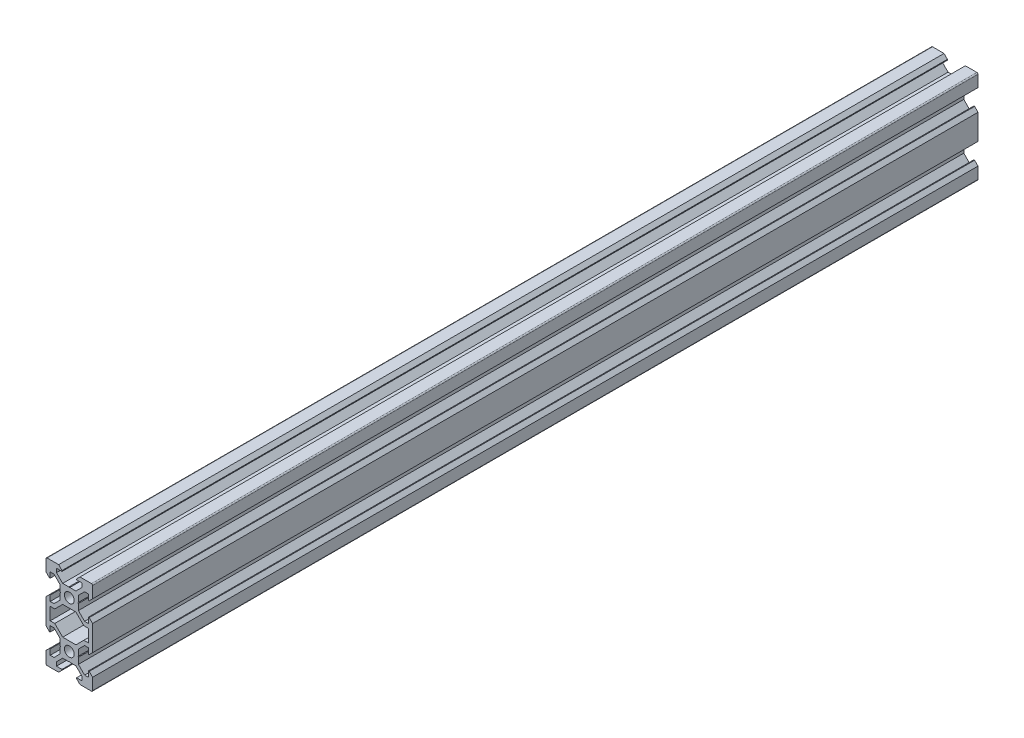
SolidWorks part; units mm, degrees
ref_plane "Front Plane" through (0, 0, 0) normal (0, 0, 1) x (1, 0, 0)
ref_plane "Top Plane" through (0, 0, 0) normal (0, 1, 0) x (1, 0, 0)
ref_plane "Right Plane" through (0, 0, 0) normal (1, 0, 0) x (0, 0, -1)
sketch "Sketch2" plane through (0, 0, 0) normal (0, 0, 1) x (1, 0, 0)
  line L106 (-6.1325, -2.3442) -> (-2.7325, -5.7442)
  line L107 (-8.0932, -2.3442) -> (-6.1325, -2.3442)
  line L108 (-8.0932, -2.3442) -> (-8.0932, 3.0558)
  line L109 (-8.0932, 3.0558) -> (-6.1325, 3.0558)
  line L110 (-6.1325, 3.0558) -> (-2.7325, 6.4558)
  line L111 (-2.7325, 6.4558) -> (2.9461, 6.4558)
  line L112 (6.3461, 3.0558) -> (2.9461, 6.4558)
  line L113 (8.3068, 3.0558) -> (6.3461, 3.0558)
  line L114 (8.3068, -2.3442) -> (8.3068, 3.0558)
  line L115 (8.3068, -2.3442) -> (6.3461, -2.3442)
  line L116 (6.3461, -2.3442) -> (2.9461, -5.7442)
  line L117 (-2.7325, -5.7442) -> (2.9461, -5.7442)
  line L118 (4.0068, 10.1458) -> (3.7968, 10.3558)
  line L119 (3.7968, 10.3558) -> (4.0068, 10.5658)
  line L120 (4.0068, 10.5658) -> (4.0068, 13.1951)
  line L121 (4.0068, 13.1951) -> (6.6675, 15.8558)
  line L122 (6.6675, 15.8558) -> (8.3068, 15.8558)
  line L123 (8.3068, 15.8558) -> (8.3068, 13.4808)
  line L124 (8.3068, 13.4808) -> (8.6518, 13.4808)
  line L125 (8.6518, 13.4808) -> (10.1068, 14.9358)
  line L126 (10.1068, 14.9358) -> (10.1068, 19.8558)
  line L127 (9.6068, 20.3558) -> (4.6868, 20.3558)
  line L128 (4.6868, 20.3558) -> (3.2318, 18.9008)
  line L129 (3.2318, 18.9008) -> (3.2318, 18.5558)
  line L130 (3.2318, 18.5558) -> (5.6068, 18.5558)
  line L131 (5.6068, 18.5558) -> (5.6068, 16.9165)
  line L132 (5.6068, 16.9165) -> (2.9461, 14.2558)
  line L133 (2.9461, 14.2558) -> (0.3168, 14.2558)
  line L134 (0.3168, 14.2558) -> (0.1068, 14.0458)
  line L135 (0.1068, 14.0458) -> (-0.1032, 14.2558)
  line L136 (-0.1032, 14.2558) -> (-2.7325, 14.2558)
  line L137 (-2.7325, 14.2558) -> (-5.3932, 16.9165)
  line L138 (-5.3932, 16.9165) -> (-5.3932, 18.5558)
  line L139 (-5.3932, 18.5558) -> (-3.0182, 18.5558)
  line L140 (-3.0182, 18.5558) -> (-3.0182, 18.9008)
  line L141 (-3.0182, 18.9008) -> (-4.4732, 20.3558)
  line L142 (-4.4732, 20.3558) -> (-9.3932, 20.3558)
  line L143 (-9.8932, 19.8558) -> (-9.8932, 14.9358)
  line L144 (-9.8932, 14.9358) -> (-8.4382, 13.4808)
  line L145 (-8.4382, 13.4808) -> (-8.0932, 13.4808)
  line L146 (-8.0932, 13.4808) -> (-8.0932, 15.8558)
  line L147 (-8.0932, 15.8558) -> (-6.4539, 15.8558)
  line L148 (-6.4539, 15.8558) -> (-3.7932, 13.1951)
  line L149 (-3.7932, 13.1951) -> (-3.7932, 10.5658)
  line L150 (-3.7932, 10.5658) -> (-3.5832, 10.3558)
  line L151 (-3.5832, 10.3558) -> (-3.7932, 10.1458)
  line L152 (-3.7932, 10.1458) -> (-3.7932, 7.5165)
  line L153 (-3.7932, 7.5165) -> (-6.4539, 4.8558)
  line L154 (-6.4539, 4.8558) -> (-8.0932, 4.8558)
  line L155 (-8.0932, 4.8558) -> (-8.0932, 7.2308)
  line L156 (-8.0932, 7.2308) -> (-8.4382, 7.2308)
  line L157 (-8.4382, 7.2308) -> (-9.8932, 5.7758)
  line L158 (-9.8932, 5.7758) -> (-9.8932, -5.0642)
  line L159 (-9.8932, -5.0642) -> (-8.4382, -6.5192)
  line L160 (-8.4382, -6.5192) -> (-8.0932, -6.5192)
  line L161 (-8.0932, -6.5192) -> (-8.0932, -4.1442)
  line L162 (-8.0932, -4.1442) -> (-6.4539, -4.1442)
  line L163 (-6.4539, -4.1442) -> (-3.7932, -6.8049)
  line L164 (-3.7932, -6.8049) -> (-3.7932, -9.4342)
  line L165 (-3.7932, -9.4342) -> (-3.5832, -9.6442)
  line L166 (-3.5832, -9.6442) -> (-3.7932, -9.8542)
  line L167 (-3.7932, -9.8542) -> (-3.7932, -12.4835)
  line L168 (-3.7932, -12.4835) -> (-6.4539, -15.1442)
  line L169 (-6.4539, -15.1442) -> (-8.0932, -15.1442)
  line L170 (-8.0932, -15.1442) -> (-8.0932, -12.7692)
  line L171 (-8.0932, -12.7692) -> (-8.4382, -12.7692)
  line L172 (-8.4382, -12.7692) -> (-9.8932, -14.2242)
  line L173 (-9.8932, -14.2242) -> (-9.8932, -19.1442)
  line L174 (-9.3932, -19.6442) -> (-4.4732, -19.6442)
  line L175 (-4.4732, -19.6442) -> (-3.0182, -18.1892)
  line L176 (-3.0182, -18.1892) -> (-3.0182, -17.8442)
  line L177 (-3.0182, -17.8442) -> (-5.3932, -17.8442)
  line L178 (-5.3932, -17.8442) -> (-5.3932, -16.2049)
  line L179 (-5.3932, -16.2049) -> (-2.7325, -13.5442)
  line L180 (-2.7325, -13.5442) -> (-0.1032, -13.5442)
  line L181 (-0.1032, -13.5442) -> (0.1068, -13.3342)
  line L182 (0.1068, -13.3342) -> (0.3168, -13.5442)
  line L183 (0.3168, -13.5442) -> (2.9461, -13.5442)
  line L184 (2.9461, -13.5442) -> (5.6068, -16.2049)
  line L185 (5.6068, -16.2049) -> (5.6068, -17.8442)
  line L186 (5.6068, -17.8442) -> (3.2318, -17.8442)
  line L187 (3.2318, -17.8442) -> (3.2318, -18.1892)
  line L188 (3.2318, -18.1892) -> (4.6868, -19.6442)
  line L189 (4.6868, -19.6442) -> (9.6068, -19.6442)
  line L190 (10.1068, -19.1442) -> (10.1068, -14.2242)
  line L191 (10.1068, -14.2242) -> (8.6518, -12.7692)
  line L192 (8.6518, -12.7692) -> (8.3068, -12.7692)
  line L193 (8.3068, -12.7692) -> (8.3068, -15.1442)
  line L194 (8.3068, -15.1442) -> (6.6675, -15.1442)
  line L195 (6.6675, -15.1442) -> (4.0068, -12.4835)
  line L196 (4.0068, -12.4835) -> (4.0068, -9.8542)
  line L197 (4.0068, -9.8542) -> (3.7968, -9.6442)
  line L198 (3.7968, -9.6442) -> (4.0068, -9.4342)
  line L199 (4.0068, -9.4342) -> (4.0068, -6.8049)
  line L200 (4.0068, -6.8049) -> (6.6675, -4.1442)
  line L201 (6.6675, -4.1442) -> (8.3068, -4.1442)
  line L202 (8.3068, -4.1442) -> (8.3068, -6.5192)
  line L203 (8.3068, -6.5192) -> (8.6518, -6.5192)
  line L204 (8.6518, -6.5192) -> (10.1068, -5.0642)
  line L205 (10.1068, -5.0642) -> (10.1068, 5.7758)
  line L206 (10.1068, 5.7758) -> (8.6518, 7.2308)
  line L207 (8.6518, 7.2308) -> (8.3068, 7.2308)
  line L208 (8.3068, 7.2308) -> (8.3068, 4.8558)
  line L209 (8.3068, 4.8558) -> (6.6675, 4.8558)
  line L210 (6.6675, 4.8558) -> (4.0068, 7.5165)
  line L211 (4.0068, 7.5165) -> (4.0068, 10.1458)
  circle A4 centre (0.1068, -9.6442) radius 2.1
  circle A5 centre (0.1068, 10.3558) radius 2.1
  arc A6 (10.1068, 19.8558) -> (9.6068, 20.3558) centre (9.6068, 19.8558) ccw
  arc A7 (-9.3932, 20.3558) -> (-9.8932, 19.8558) centre (-9.3932, 19.8558) ccw
  arc A8 (-9.8932, -19.1442) -> (-9.3932, -19.6442) centre (-9.3932, -19.1442) ccw
  arc A9 (9.6068, -19.6442) -> (10.1068, -19.1442) centre (9.6068, -19.1442) ccw
extrude "Boss-Extrude1" add sketch "Sketch2" along normal blind 380
